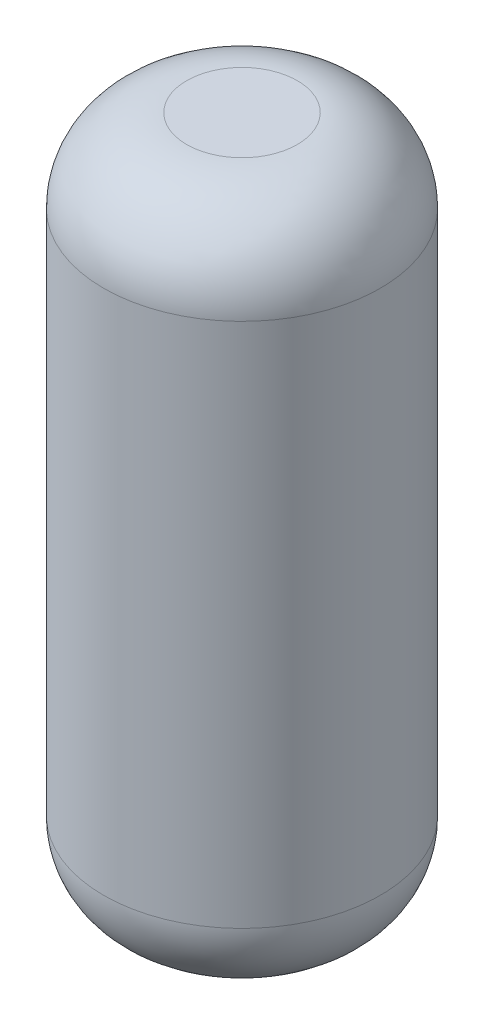
SolidWorks part; units mm, degrees
material "AISI 1045 Steel, cold drawn"
ref_plane "Front Plane" through (0, 0, 0) normal (0, 0, 1) x (1, 0, 0)
ref_plane "Top Plane" through (0, 0, 0) normal (0, 1, 0) x (1, 0, 0)
ref_plane "Right Plane" through (0, 0, 0) normal (1, 0, 0) x (0, 0, -1)
sketch "Sketch1" plane through (0, 0, 0) normal (0, 1, 0) x (1, 0, 0)
  circle A0 centre (0, 0) radius 5
extrude "Boss-Extrude1" add sketch "Sketch1" along normal blind 25
fillet "Fillet2" radius 3 2 edges at (0, 0, 5) (0, 25, 5)
